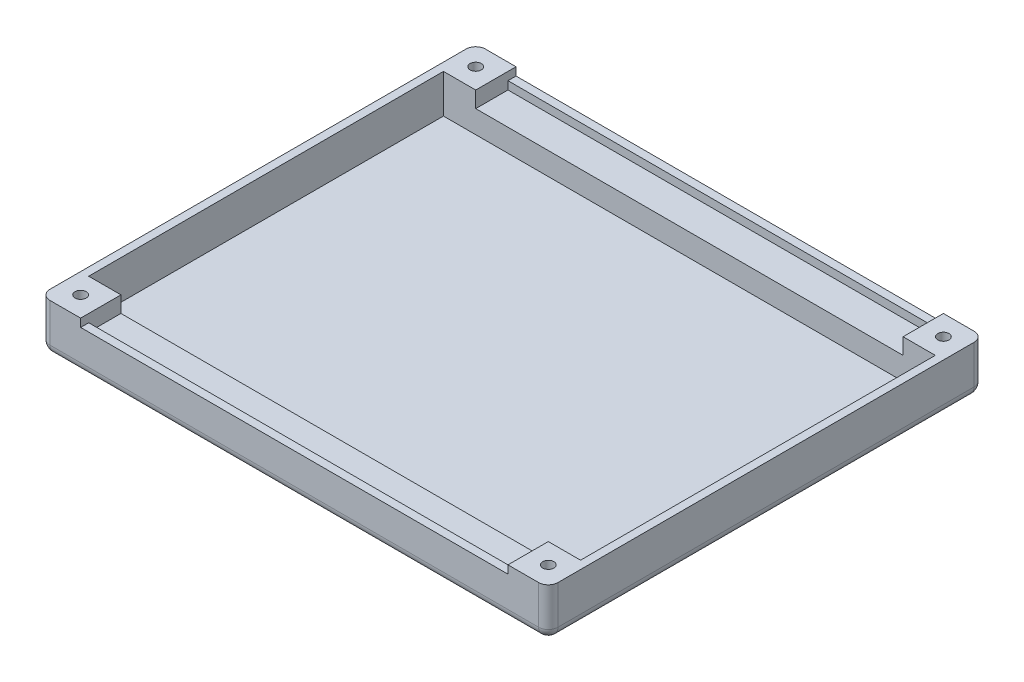
SolidWorks part; units mm, degrees
ref_plane "Front Plane" through (0, 0, 0) normal (0, 0, 1) x (1, 0, 0)
ref_plane "Top Plane" through (0, 0, 0) normal (0, 1, 0) x (1, 0, 0)
ref_plane "Right Plane" through (0, 0, 0) normal (1, 0, 0) x (0, 0, -1)
sketch "Sketch1" plane through (0, 0, 0) normal (0, 1, 0) x (1, 0, 0)
  line L1 (-100.0125, -85.725) -> (100.0125, -85.725)
  line L2 (-100.0125, -85.725) -> (-100.0125, 85.725)
  line L3 (-100.0125, 85.725) -> (100.0125, 85.725)
  line L4 (100.0125, -85.725) -> (100.0125, 85.725)
  line L5 (-100.0125, -85.725) -> (100.0125, 85.725) construction
  line L6 (-100.0125, 85.725) -> (100.0125, -85.725) construction
  point P0 (0, 0)
  dimension "D1" = 200.025
  dimension "D2" = 171.45
extrude "Boss-Extrude1" add sketch "Sketch1" along normal blind 19.05
sketch "Sketch2" plane through (0, 19.05, 0) normal (0, 1, 0) x (1, 0, 0)
  line L0 (100.0125, -85.725) -> (100.0125, 85.725) construction
  line L1 (-96.8375, -69.85) -> (96.8375, -69.85)
  line L2 (-96.8375, -69.85) -> (-96.8375, 69.85)
  line L3 (-96.8375, 69.85) -> (96.8375, 69.85)
  line L4 (96.8375, -69.85) -> (96.8375, 69.85)
  line L5 (-96.8375, -69.85) -> (96.8375, 69.85) construction
  line L6 (-96.8375, 69.85) -> (96.8375, -69.85) construction
  line L7 (-100.0125, -85.725) -> (100.0125, -85.725) construction
  point P0 (0, 0)
  dimension "D1" = 3.175
  dimension "D2" = 15.875
extrude "Cut-Extrude1" cut sketch "Sketch2" against normal offset from surface (15.24 mm away) 3.81 up to face at (0, 0, 0)
sketch "Sketch4" plane through (0, 19.05, 0) normal (0, 1, 0) x (1, 0, 0)
  line L8 (100.0125, 85.725) -> (-100.0125, 85.725) construction
  line L9 (-84.1375, -85.725) -> (84.1375, -85.725)
  line L10 (-84.1375, -85.725) -> (-84.1375, 85.725)
  line L11 (-84.1375, 85.725) -> (84.1375, 85.725)
  line L12 (84.1375, -85.725) -> (84.1375, 85.725)
  line L13 (-84.1375, -85.725) -> (84.1375, 85.725) construction
  line L14 (-84.1375, 85.725) -> (84.1375, -85.725) construction
  line L15 (100.0125, -85.725) -> (100.0125, 85.725) construction
  point P0 (0, 0)
  dimension "D1" = 15.875
extrude "Cut-Extrude2" cut sketch "Sketch4" against normal blind 3.175
sketch "Sketch5" plane through (0, 15.875, 0) normal (0, 1, 0) x (1, 0, 0)
  line L0 (-96.8375, -69.85) -> (96.8375, -69.85) construction
  line L1 (-84.1375, -69.85) -> (84.1375, -69.85)
  line L2 (-84.1375, -69.85) -> (-84.1375, -82.55)
  line L3 (-84.1375, -82.55) -> (84.1375, -82.55)
  line L4 (84.1375, -69.85) -> (84.1375, -82.55)
  line L6 (-84.1375, -69.85) -> (-84.1375, -85.725) construction
  line L7 (84.1375, -85.725) -> (84.1375, -69.85) construction
  dimension "D1" = 12.7
extrude "Cut-Extrude3" cut sketch "Sketch5" against normal blind 3.175
sketch "Sketch7" plane through (0, 15.875, 0) normal (0, 1, 0) x (1, 0, 0)
  line L1 (-84.1375, 82.55) -> (84.1375, 82.55)
  line L2 (-84.1375, 82.55) -> (-84.1375, 69.85)
  line L3 (-84.1375, 69.85) -> (84.1375, 69.85)
  line L4 (84.1375, 82.55) -> (84.1375, 69.85)
  line L5 (-84.1375, 85.725) -> (-84.1375, 69.85) construction
  line L6 (84.1375, 69.85) -> (-84.1375, 69.85) construction
  line L7 (84.1375, 69.85) -> (84.1375, 85.725) construction
  dimension "D1" = 12.7
extrude "Cut-Extrude5" cut sketch "Sketch7" against normal blind 3.175
sketch "Sketch11" plane through (0, 19.05, 0) normal (0, 1, 0) x (1, 0, 0)
  line L0 (100.0125, 85.725) -> (84.1375, 85.725) construction
  line L3 (92.075, 77.7875) -> (84.1375, 77.7875) construction
  line L9 (84.1375, 69.85) -> (84.1375, 85.725) construction
  line L10 (0, 0) -> (96.8375, 0) construction
  line L11 (96.8375, -69.85) -> (96.8375, 69.85) construction
  line L12 (92.075, -77.7875) -> (84.1375, -77.7875) construction
  circle A2 centre (92.075, 77.7875) radius 2.2
  circle A4 centre (92.075, -77.7875) radius 2.2
  point P1 (110.31, 95.31)
  point P4 (92.075, 85.725)
  dimension "D1" = 4.4
extrude "Cut-Extrude6" cut sketch "Sketch11" against normal blind 33.5
fillet "Fillet3" radius 3.81 8 edges at (-100.0125, 9.525, 85.725) (0, 0, 85.725) (100.0125, 9.525, 85.725) (100.0125, 0, 0) (100.0125, 9.525, -85.725) (0, 0, -85.725) (-100.0125, 9.525, -85.725) (-100.0125, 0, 0)
mirror "Mirror1" about plane through (0, 0, 0) normal (1, 0, 0) of "Cut-Extrude6"
